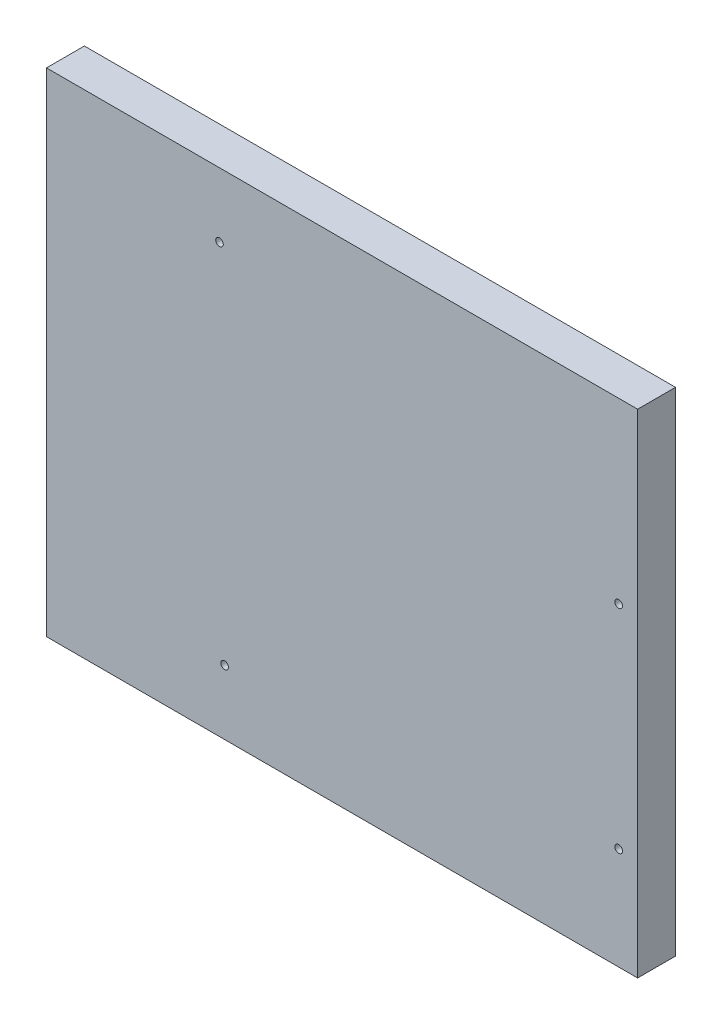
SolidWorks part; units mm, degrees
material "Acero al carbono no aleado"
ref_plane "Alzado" through (0, 0, 0) normal (0, 0, 1) x (1, 0, 0)
ref_plane "Planta" through (0, 0, 0) normal (0, 1, 0) x (1, 0, 0)
ref_plane "Vista lateral" through (0, 0, 0) normal (1, 0, 0) x (0, 0, -1)
sketch "Croquis1" plane through (0, 0, 0) normal (0, 0, 1) x (1, 0, 0)
  line L1 (0, 0) -> (78, 0)
  line L2 (0, 0) -> (0, 65)
  line L3 (0, 65) -> (78, 65)
  line L4 (78, 0) -> (78, 65)
  dimension "D1" = 65
  dimension "D2" = 78
extrude "Saliente-Extruir2" add sketch "Croquis1" along normal blind 5
sketch "Croquis3" plane through (0, 0, 5) normal (0, 0, 1) x (1, 0, 0)
  line L0 (78, 0) -> (78, 65) construction
  line L1 (78, 6) -> (0, 6)
  line L2 (78, 6) -> (78, 59)
  line L3 (78, 59) -> (0, 59)
  line L4 (0, 6) -> (0, 59)
  line L5 (0, 65) -> (0, 0) construction
  line L6 (76, 70.766) -> (10, 70.766) construction
  line L7 (0, 0) -> (78, 0) construction
  line L8 (78, 65) -> (0, 65) construction
  line L9 (78, 65) -> (0, 65) construction
  line L10 (75.5, 43) -> (75.5, 41.5) construction
  line L11 (78, 57) -> (0, 57) construction
  line L12 (76, 65) -> (76, 0) construction
  line L13 (78, 7.25) -> (-4.2976, 7.25) construction
  line L14 (78, 8) -> (-1.5445, 8) construction
  line L15 (78, 10) -> (76, 8)
  line L16 (78, 10) -> (78, 43)
  line L17 (78, 43) -> (75, 46.5)
  line L18 (75, 46.5) -> (75, 59)
  line L19 (10, 70.766) -> (10, -4.7219) construction
  line L20 (10, 59) -> (10, 50)
  line L21 (10, 50) -> (4, 50)
  line L22 (4, 50) -> (4, 39)
  line L23 (4, 39) -> (10, 39)
  line L24 (10, 39) -> (10, 19)
  line L25 (10, 19) -> (9, 19)
  line L26 (9, 19) -> (9, 11)
  line L27 (9, 11) -> (10, 11)
  line L28 (10, 11) -> (10, 6)
  line L29 (75.5, 59) -> (75.5, 43) construction
  line L30 (77, 41.5) -> (78, 41.5) construction
  line L31 (76, 8) -> (76, 6)
  line L32 (10, 58) -> (36.7696, 58) construction
  circle A0 centre (22.8272, 56.5) radius 1.5
  circle A1 centre (75.5, 41.5) radius 0.5
  circle A2 centre (23.5, 8.5) radius 1.5
  circle A3 centre (75.5, 13.5) radius 0.5
  circle A4 centre (22.8272, 56.5) radius 0.5
  circle A5 centre (23.5, 8.5) radius 0.5
  point P12 (39, 65)
  point P15 (39, 0)
  dimension "D14" = 1
  dimension "D12" = 1
  dimension "D16" = 2.5
  dimension "D17" = 1
  dimension "D18" = 7.5
  dimension "D21" = 2.5
  dimension "D23" = 3
  dimension "D25" = 2.5
  dimension "D26" = 3
  dimension "D27" = 68
  dimension "D34" = 1
  dimension "D35" = 1
  dimension "D1" = 65
  dimension "D2" = 53
  dimension "D3" = 6
  dimension "D4" = 16
  dimension "D5" = 2
  dimension "D6" = 2
  dimension "D7" = 2.5
  dimension "D8" = 40.601
  dimension "D9" = 33
  dimension "D10" = 2
  dimension "D11" = 12.5
  dimension "D13" = 1.5
  dimension "D15" = 3
  dimension "D19" = 9
  dimension "D20" = 1
  dimension "D22" = 22.8272
  dimension "D24" = 13.5
  dimension "D28" = 11
  dimension "D29" = 6
  dimension "D30" = 1
  dimension "D31" = 8
  dimension "D32" = 1
  dimension "D33" = 5
extrude "Cortar-Extruir1" cut sketch "Croquis3" against normal blind 21 contours A4 | A5 | A3 | A1
